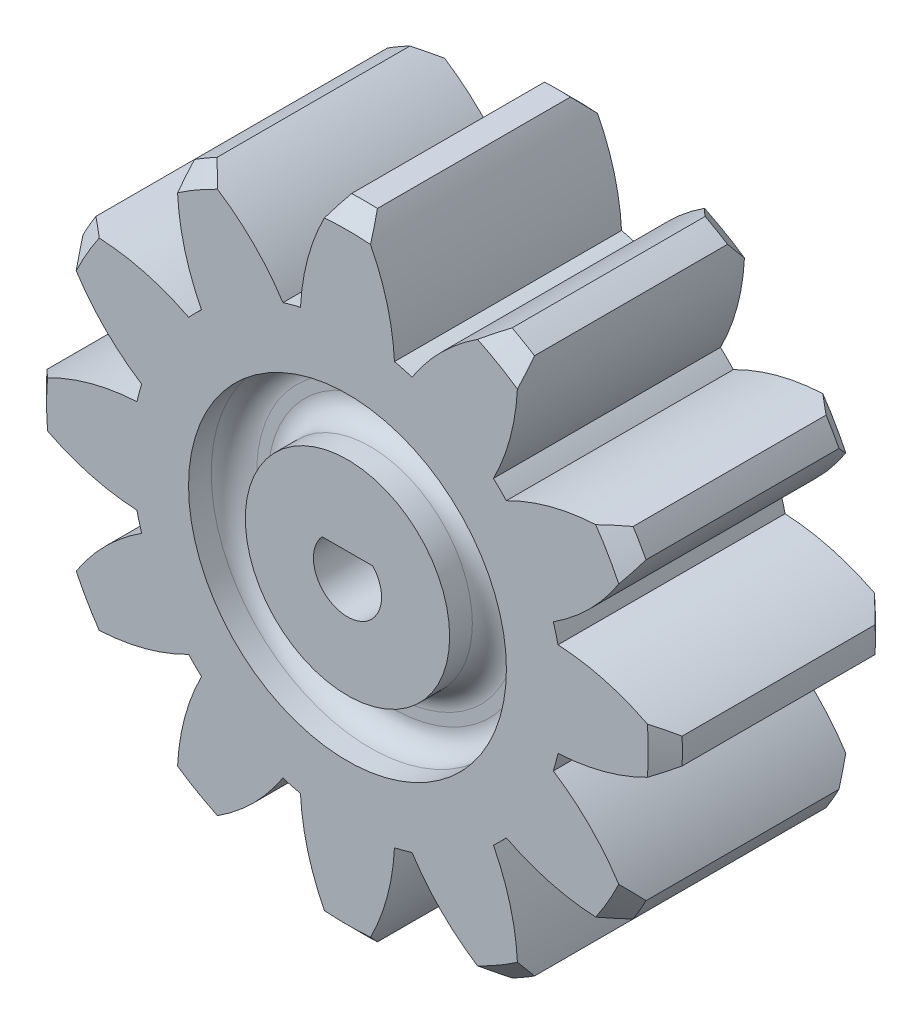
SolidWorks part; units mm, degrees
ref_plane "Front Plane" through (0, 0, 0) normal (0, 0, 1) x (1, 0, 0)
ref_plane "Top Plane" through (0, 0, 0) normal (0, 1, 0) x (1, 0, 0)
ref_plane "Right Plane" through (0, 0, 0) normal (1, 0, 0) x (0, 0, -1)
sketch "Sketch1" plane through (0, 0, 0) normal (0, 0, 1) x (1, 0, 0)
  line L0 (0, 18.2844) -> (0, -18.5063) construction
  line L1 (-21.4042, 0) -> (32.7718, 0) construction
  line L2 (-1.57, 17.3282) -> (-1.57, 3.0678) construction
  line L3 (-0.57, 19.83) -> (-0.57, 2.7238) construction
  line L4 (-2.07, 15.9554) -> (-2.07, 3.2392) construction
  circle A0 centre (0, 0) radius 9.5
  circle A1 centre (0, 0) radius 12 construction
  circle A2 centre (0, 0) radius 14
  arc A3 (-2.07, 9.2717) -> (-0.57, 13.9884) centre (7.6252, 8.7853) cw
  arc A4 (2.07, 9.2717) -> (0.57, 13.9884) centre (-7.6252, 8.7853) ccw
  point P18 (-1.57, 11.8969)
  point P19 (0, 0)
  dimension "D1" = 19
  dimension "D2" = 24
  dimension "D3" = 28
  dimension "D4" = 1.57
  dimension "D5" = 1
  dimension "D6" = 0.5
extrude "Boss-Extrude1" add sketch "Sketch1" along normal blind 10 contours A0 | A0 A4 A2 A3
chamfer "Chamfer1" distance 0.75 angle 45 2 edges at (0, 14, 0) (0, 14, 10)
pattern_circular "CirPattern1" count 12 over 360 about axis through (0, 0, 0) along (0, 0, 1) of "Boss-Extrude1", "Chamfer1"
sketch "Sketch2" plane through (0, 0, 10) normal (0, 0, 1) x (1, 0, 0)
  circle A0 centre (0, 0) radius 7
  circle A1 centre (0, 0) radius 4.5
  dimension "D1" = 14
  dimension "D2" = 9
extrude "Cut-Extrude1" cut sketch "Sketch2" against normal blind 2
fillet "Fillet1" radius 1 2 edges at (7, 0, 8) (4.5, 0, 8)
ref_plane "Plane1" through (0, 0, 5) normal (0, 0, 1) x (1, 0, 0)
mirror "Mirror1" about plane through (0, 0, 5) normal (0, 0, 1) of "Fillet1", "Cut-Extrude1"
sketch "Sketch3" plane through (0, 0, 10) normal (0, 0, 1) x (1, 0, 0)
  line L0 (-1.118, 1) -> (1.118, 1)
  circle A0 centre (0, 0) radius 1.5
  dimension "D1" = 3
  dimension "D2" = 2.5
extrude "Cut-Extrude2" cut sketch "Sketch3" against normal up to next contours L0 A0
